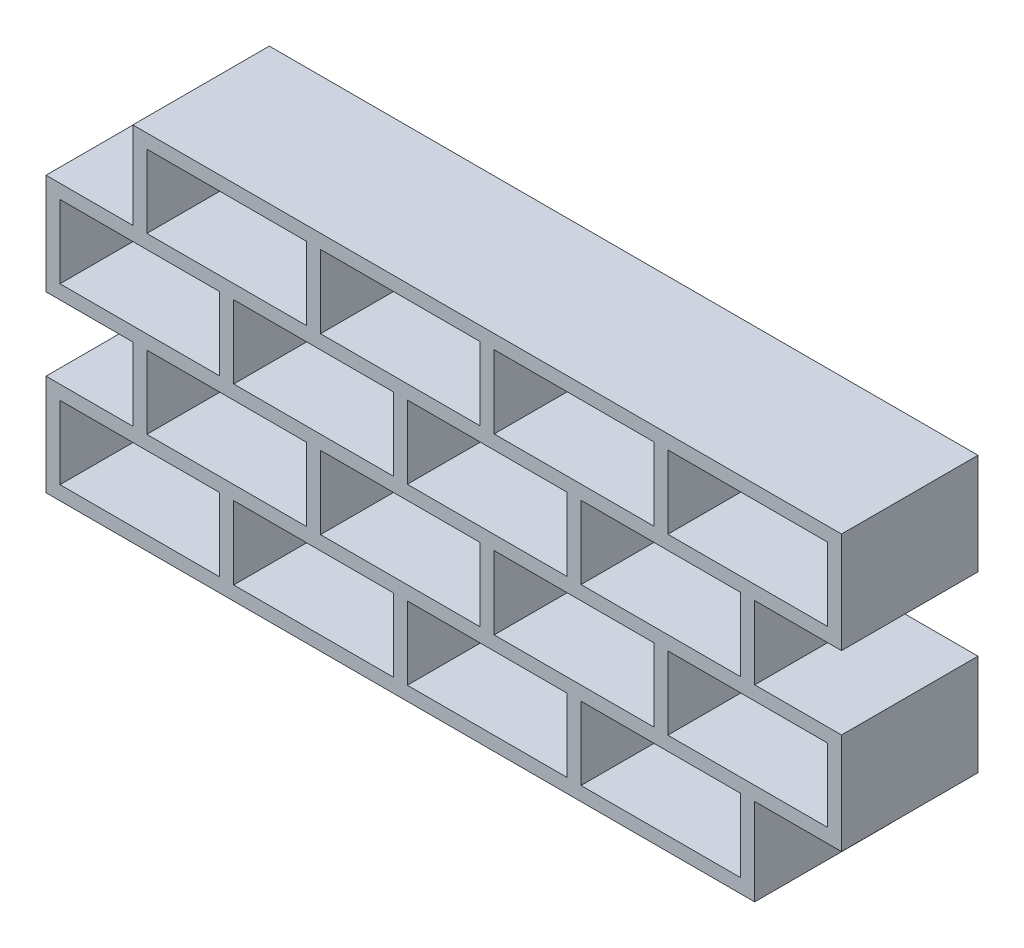
SolidWorks part; units mm, degrees
ref_plane "前视基准面" through (0, 0, 0) normal (0, 0, 1) x (1, 0, 0)
ref_plane "上视基准面" through (0, 0, 0) normal (0, 1, 0) x (1, 0, 0)
ref_plane "右视基准面" through (0, 0, 0) normal (1, 0, 0) x (0, 0, -1)
sketch "草图1" plane through (0, 0, 0) normal (0, 0, 1) x (1, 0, 0)
  line L0 (-2.75, -1.48) -> (2.75, -1.48)
  line L1 (-2.545, -1.275) -> (2.545, -1.275) construction
  line L2 (-2.545, -1.275) -> (-2.545, 1.275) construction
  line L3 (-2.545, 1.275) -> (2.545, 1.275) construction
  line L4 (2.545, -1.275) -> (2.545, 1.275) construction
  line L5 (0, 1.275) -> (0, -1.275) construction
  line L6 (-2.545, 0) -> (2.545, 0) construction
  line L8 (-2.75, 1.48) -> (-0.205, 1.48)
  line L9 (-2.75, -1.48) -> (-2.75, 1.48)
  line L10 (-0.205, 1.07) -> (-0.205, -1.07)
  line L11 (-2.545, -0.205) -> (2.34, -0.205)
  line L12 (-2.34, -1.07) -> (2.34, -1.07)
  line L13 (2.34, -1.07) -> (2.34, 1.07)
  line L14 (-2.34, 1.07) -> (2.34, 1.07)
  line L15 (-2.34, -1.07) -> (-2.34, 1.07)
  line L16 (0.205, 1.07) -> (0.205, -1.07)
  line L17 (-2.545, 0.205) -> (2.34, 0.205)
  line L18 (2.34, -1.48) -> (7.84, -1.48)
  line L20 (2.75, 1.48) -> (4.885, 1.48)
  line L22 (4.885, 1.07) -> (4.885, -1.07)
  line L23 (2.75, -0.205) -> (7.43, -0.205)
  line L24 (2.75, -1.07) -> (7.43, -1.07)
  line L25 (7.43, -1.07) -> (7.43, 1.07)
  line L26 (2.75, 1.07) -> (7.43, 1.07)
  line L27 (2.75, -1.07) -> (2.75, 1.07)
  line L28 (5.295, 1.07) -> (5.295, -1.07)
  line L29 (2.75, 0.205) -> (7.43, 0.205)
  line L30 (2.545, -1.275) -> (7.635, -1.275) construction
  line L31 (2.545, -1.275) -> (2.545, 1.275) construction
  line L32 (2.34, 1.275) -> (7.635, 1.275) construction
  line L33 (7.635, -1.275) -> (7.635, 1.275) construction
  line L34 (5.09, 1.275) -> (5.09, -1.275) construction
  line L35 (2.545, 0) -> (7.635, 0) construction
  line L36 (7.43, -1.48) -> (12.93, -1.48)
  line L38 (7.84, 1.48) -> (9.975, 1.48)
  line L40 (9.975, 1.07) -> (9.975, -1.07)
  line L41 (7.84, -0.205) -> (12.52, -0.205)
  line L42 (7.84, -1.07) -> (12.52, -1.07)
  line L43 (12.52, -1.07) -> (12.52, 1.07)
  line L44 (7.84, 1.07) -> (12.52, 1.07)
  line L45 (7.84, -1.07) -> (7.84, 1.07)
  line L46 (10.385, 1.07) -> (10.385, -1.07)
  line L47 (7.84, 0.205) -> (12.52, 0.205)
  line L48 (7.635, -1.275) -> (12.725, -1.275) construction
  line L49 (7.635, -1.275) -> (7.635, 1.275) construction
  line L50 (7.635, 1.275) -> (12.725, 1.275) construction
  line L51 (12.725, -1.275) -> (12.725, 1.275) construction
  line L52 (10.18, 1.275) -> (10.18, -1.275) construction
  line L53 (7.635, 0) -> (12.725, 0) construction
  line L54 (12.52, -1.48) -> (18.02, -1.48)
  line L55 (18.02, -1.48) -> (18.02, 1.07)
  line L56 (12.93, 1.48) -> (15.065, 1.48)
  line L58 (15.065, 1.07) -> (15.065, -1.07)
  line L59 (12.725, -0.205) -> (17.61, -0.205)
  line L60 (12.93, -1.07) -> (17.61, -1.07)
  line L61 (17.61, -1.07) -> (17.61, 1.07)
  line L62 (12.93, 1.07) -> (17.61, 1.07)
  line L63 (12.93, -1.07) -> (12.93, 1.07)
  line L64 (15.475, 1.07) -> (15.475, -1.07)
  line L65 (12.93, 0.205) -> (17.61, 0.205)
  line L66 (12.725, -1.275) -> (17.815, -1.275) construction
  line L67 (12.725, -1.275) -> (12.725, 1.275) construction
  line L68 (12.725, 1.275) -> (17.815, 1.275) construction
  line L69 (17.815, -1.275) -> (17.815, 1.275) construction
  line L70 (15.27, 1.275) -> (15.27, -1.275) construction
  line L71 (12.725, 0) -> (17.815, 0) construction
  line L72 (2.75, -1.48) -> (2.75, 1.48) construction
  line L73 (-2.545, 0.205) -> (2.545, 0.205) construction
  line L74 (-2.545, -0.205) -> (2.545, -0.205) construction
  line L75 (2.34, -1.07) -> (2.34, 1.07)
  line L76 (2.34, -1.48) -> (2.34, -1.275) [skipped]
  line L77 (2.75, -1.07) -> (2.75, 1.07)
  line L78 (12.52, -1.07) -> (12.52, 1.07)
  line L79 (12.93, -1.07) -> (12.93, 1.07)
  line L80 (12.52, -1.48) -> (12.52, -1.275) [skipped]
  line L81 (7.43, -1.07) -> (7.43, 1.07)
  line L82 (7.43, -1.48) -> (7.43, -1.275) [skipped]
  line L83 (7.84, -1.07) -> (7.84, 1.07)
  line L84 (-0.205, 1.275) -> (-0.205, -1.275) construction
  line L85 (0.205, 1.275) -> (0.205, -1.275) construction
  line L86 (-2.75, 3.62) -> (-0.205, 3.62)
  line L87 (-2.75, 6.58) -> (-0.205, 6.58)
  line L88 (-2.75, 3.62) -> (-2.75, 6.58)
  line L91 (-2.34, 4.03) -> (-0.205, 4.03)
  line L92 (2.34, 4.03) -> (2.34, 4.895)
  line L93 (-2.34, 6.17) -> (-0.205, 6.17)
  line L94 (-2.34, 4.03) -> (-2.34, 4.895)
  line L95 (-0.205, 6.17) -> (0.205, 6.17)
  line L97 (2.75, 3.62) -> (4.885, 3.62)
  line L98 (2.75, 6.58) -> (4.885, 6.58)
  line L99 (-2.34, 5.305) -> (-2.34, 4.895)
  line L100 (-0.205, 4.03) -> (0.205, 4.03)
  line L101 (2.75, 4.03) -> (4.885, 4.03)
  line L102 (7.43, 4.03) -> (7.43, 4.895)
  line L103 (2.75, 6.17) -> (4.885, 6.17)
  line L104 (2.75, 4.03) -> (2.75, 4.895)
  line L105 (4.885, 7.855) -> (4.885, 7.445)
  line L106 (5.295, 7.855) -> (5.295, 7.445)
  line L107 (7.84, 3.62) -> (9.975, 3.62)
  line L108 (7.84, 6.58) -> (9.975, 6.58)
  line L109 (7.43, 8.72) -> (7.84, 8.72)
  line L110 (9.975, 7.855) -> (9.975, 7.445)
  line L111 (7.84, 4.03) -> (9.975, 4.03)
  line L112 (12.52, 4.03) -> (12.52, 4.895)
  line L113 (7.84, 6.17) -> (9.975, 6.17)
  line L114 (7.84, 4.03) -> (7.84, 4.895)
  line L115 (7.43, 6.58) -> (7.84, 6.58)
  line L116 (10.385, 7.855) -> (10.385, 7.445)
  line L117 (12.93, 3.62) -> (15.065, 3.62)
  line L118 (20.155, 2.755) -> (20.155, 3.62)
  line L119 (12.93, 6.58) -> (15.065, 6.58)
  line L120 (12.52, 8.72) -> (12.93, 8.72)
  line L121 (15.065, 7.855) -> (15.065, 7.445)
  line L122 (12.93, 4.03) -> (15.065, 4.03)
  line L123 (17.61, 4.03) -> (17.61, 4.895)
  line L124 (12.93, 6.17) -> (15.065, 6.17)
  line L125 (12.93, 4.03) -> (12.93, 4.895)
  line L126 (12.52, 6.58) -> (12.93, 6.58)
  line L127 (15.475, 7.855) -> (15.475, 7.445)
  line L128 (2.34, 4.03) -> (2.34, 4.895)
  line L129 (2.75, 4.03) -> (2.75, 4.895)
  line L130 (12.52, 4.03) -> (12.52, 4.895)
  line L131 (12.93, 4.03) -> (12.93, 4.895)
  line L132 (7.43, 4.03) -> (7.43, 4.895)
  line L133 (7.84, 4.03) -> (7.84, 4.895)
  line L134 (-2.545, 3.825) -> (2.545, 3.825) construction
  line L135 (-2.545, 3.825) -> (-2.545, 6.375) construction
  line L136 (-2.545, 6.375) -> (2.545, 6.375) construction
  line L137 (2.545, 3.825) -> (2.545, 6.375) construction
  line L138 (17.61, 8.72) -> (18.02, 8.72)
  line L139 (17.61, 6.58) -> (18.02, 6.58)
  line L140 (2.545, 3.825) -> (7.635, 3.825) construction
  line L141 (2.545, 3.825) -> (2.545, 6.375) construction
  line L142 (2.34, 6.375) -> (7.635, 6.375) construction
  line L143 (7.635, 3.825) -> (7.635, 6.375) construction
  line L144 (17.61, 5.305) -> (17.61, 4.895)
  line L145 (15.475, 6.17) -> (15.065, 6.17)
  line L146 (7.635, 3.825) -> (12.725, 3.825) construction
  line L147 (7.635, 3.825) -> (7.635, 6.375) construction
  line L148 (7.635, 6.375) -> (12.725, 6.375) construction
  line L149 (12.725, 3.825) -> (12.725, 6.375) construction
  line L150 (12.93, 5.305) -> (12.93, 4.895)
  line L151 (15.065, 4.03) -> (15.475, 4.03)
  line L152 (12.725, 3.825) -> (17.815, 3.825) construction
  line L153 (12.725, 3.825) -> (12.725, 6.375) construction
  line L154 (12.725, 6.375) -> (17.815, 6.375) construction
  line L155 (17.815, 3.825) -> (17.815, 6.375) construction
  line L156 (12.52, 4.895) -> (12.52, 5.305)
  line L157 (10.385, 6.17) -> (9.975, 6.17)
  line L158 (15.27, 0) -> (15.27, 3.825) construction
  line L159 (7.84, 5.305) -> (7.84, 4.895)
  line L160 (10.385, 4.03) -> (12.52, 4.03)
  line L161 (4.885, 1.48) -> (4.885, 2.345)
  line L162 (0.205, 8.72) -> (2.34, 8.72)
  line L163 (15.475, 6.58) -> (15.475, 7.445)
  line L164 (9.975, 4.03) -> (10.385, 4.03)
  line L165 (2.545, 8.925) -> (2.545, 8.72) construction
  line L166 (20.36, 6.375) -> (20.36, 8.925) construction
  line L167 (0.205, 1.48) -> (2.34, 1.48)
  line L168 (4.885, 1.07) -> (10.385, 1.07)
  line L169 (7.43, 5.305) -> (7.43, 4.895)
  line L170 (20.155, 1.48) -> (20.155, 2.345)
  line L171 (4.885, 6.17) -> (5.295, 6.17)
  line L172 (15.065, 6.58) -> (15.065, 7.445)
  line L173 (10.385, 6.58) -> (10.385, 7.445)
  line L174 (15.27, 1.275) -> (20.36, 1.275) construction
  line L175 (2.75, 5.305) -> (2.75, 4.895)
  line L176 (4.885, 4.03) -> (5.295, 4.03)
  line L177 (10.385, 1.48) -> (10.385, 2.345)
  line L178 (5.295, 6.17) -> (7.43, 6.17)
  line L179 (2.34, 5.305) -> (2.34, 4.895)
  line L180 (0, 1.275) -> (5.09, 1.275) construction
  line L181 (15.27, 1.275) -> (15.27, 3.825) construction
  line L182 (15.27, 3.825) -> (20.36, 3.825) construction
  line L183 (10.18, 6.375) -> (10.18, 8.925) construction
  line L184 (2.34, 3.62) -> (2.75, 3.62)
  line L185 (5.295, 1.48) -> (7.43, 1.48)
  line L186 (9.975, 1.07) -> (15.475, 1.07)
  line L187 (4.885, 9.13) -> (10.385, 9.13)
  line L188 (0.205, 2.755) -> (0.205, 2.345)
  line L189 (15.475, 6.58) -> (17.61, 6.58)
  line L190 (15.065, 6.58) -> (15.065, 7.445)
  line L191 (5.09, 1.275) -> (5.09, 3.825) construction
  line L192 (4.885, 2.755) -> (4.885, 2.345)
  line L193 (9.975, 1.48) -> (9.975, 2.345)
  line L194 (15.475, 3.62) -> (17.61, 3.62)
  line L195 (15.475, 1.48) -> (15.475, 2.345)
  line L196 (0.205, 6.58) -> (0.205, 7.445)
  line L197 (5.295, 8.72) -> (7.43, 8.72)
  line L198 (15.065, 9.13) -> (20.565, 9.13)
  line L199 (2.34, 1.48) -> (2.75, 1.48)
  line L200 (10.18, 1.275) -> (10.18, 3.825) construction
  line L201 (10.18, 3.825) -> (15.27, 3.825) construction
  line L202 (5.295, 4.03) -> (7.43, 4.03)
  line L203 (5.295, 1.48) -> (5.295, 2.345)
  line L204 (5.295, 1.48) -> (5.295, 2.345)
  line L205 (5.295, 6.58) -> (7.43, 6.58)
  line L206 (10.385, 6.17) -> (12.52, 6.17)
  line L207 (5.295, 2.755) -> (5.295, 2.345)
  line L208 (0, 6.375) -> (5.09, 6.375) construction
  line L209 (5.09, 6.375) -> (10.18, 6.375) construction
  line L210 (15.27, 8.925) -> (20.36, 8.925) construction
  line L211 (4.885, 1.48) -> (4.885, 2.345)
  line L212 (7.43, 3.62) -> (7.84, 3.62)
  line L213 (9.975, 2.755) -> (9.975, 2.345)
  line L215 (4.885, 6.58) -> (4.885, 7.445)
  line L216 (10.385, 8.72) -> (12.52, 8.72)
  line L217 (0, 1.275) -> (0, 3.825) construction
  line L218 (7.43, 1.48) -> (7.84, 1.48)
  line L219 (5.09, 6.375) -> (5.09, 8.925) construction
  line L220 (15.27, 6.375) -> (15.27, 8.925) construction
  line L221 (0.205, 1.48) -> (0.205, 2.345)
  line L222 (5.295, 3.62) -> (7.43, 3.62)
  line L223 (10.385, 1.48) -> (12.52, 1.48)
  line L224 (10.385, 6.58) -> (10.385, 7.445)
  line L225 (20.155, 6.58) -> (20.155, 8.72)
  line L226 (4.885, 3.825) -> (10.18, 3.825) construction
  line L227 (20.36, 1.275) -> (20.36, 3.825) construction
  line L228 (17.815, 3.825) -> (17.815, 6.375) construction
  line L229 (10.385, 2.345) -> (10.385, 2.755)
  line L230 (15.065, 1.07) -> (17.61, 1.07)
  line L231 (12.52, 3.62) -> (12.93, 3.62)
  line L232 (15.475, 8.72) -> (17.61, 8.72)
  line L233 (15.475, 6.58) -> (15.475, 7.445)
  line L234 (15.065, 2.755) -> (15.065, 2.345)
  line L235 (12.52, 1.48) -> (12.93, 1.48)
  line L236 (15.27, 6.375) -> (20.36, 6.375) construction
  line L237 (0.205, 4.03) -> (2.34, 4.03)
  line L239 (9.975, 1.48) -> (9.975, 2.345)
  line L241 (10.385, 6.58) -> (12.52, 6.58)
  line L242 (15.475, 6.17) -> (17.61, 6.17)
  line L243 (15.475, 2.755) -> (15.475, 2.345)
  line L244 (15.27, 1.275) -> (15.27, 3.825) construction
  line L245 (10.18, 6.375) -> (15.27, 6.375) construction
  line L246 (15.27, 6.375) -> (15.27, 8.925) construction
  line L247 (17.61, 1.48) -> (18.02, 1.48)
  line L248 (17.61, 3.62) -> (18.02, 3.62)
  line L249 (10.385, 3.62) -> (12.52, 3.62)
  line L250 (9.975, 6.58) -> (9.975, 7.445)
  line L251 (5.295, 6.58) -> (5.295, 7.445)
  line L252 (20.155, 2.755) -> (20.155, 2.345)
  line L253 (4.885, 6.58) -> (4.885, 7.445)
  line L254 (0, 7.65) -> (0.205, 7.65) construction
  line L255 (4.885, 8.925) -> (10.18, 8.925) construction
  line L256 (15.475, 1.48) -> (17.61, 1.48)
  line L257 (15.065, 1.48) -> (15.065, 2.345)
  line L260 (0, 3.825) -> (5.09, 3.825) construction
  line L261 (5.09, 1.275) -> (10.18, 1.275) construction
  line L262 (5.09, 6.375) -> (5.09, 8.925) construction
  line L263 (2.75, 1.48) -> (4.885, 1.48)
  line L264 (0.205, 3.62) -> (2.34, 3.62)
  line L266 (15.475, 1.48) -> (15.475, 2.345)
  line L268 (10.18, 1.275) -> (10.18, 3.825) construction
  line L270 (-0.205, 1.07) -> (5.295, 1.07)
  line L274 (0.205, 6.58) -> (2.34, 6.58)
  line L276 (9.975, 6.58) -> (9.975, 7.445)
  line L279 (15.065, 1.48) -> (15.065, 2.345)
  line L280 (15.475, 4.03) -> (17.61, 4.03)
  line L281 (0.205, 6.58) -> (2.34, 6.58)
  line L285 (10.18, 1.275) -> (15.27, 1.275) construction
  line L289 (10.385, 1.48) -> (10.385, 2.345)
  line L290 (0.205, 6.17) -> (2.34, 6.17)
  line L291 (9.975, 9.13) -> (15.475, 9.13)
  line L292 (5.295, 6.58) -> (5.295, 7.445)
  line L293 (10.18, 6.375) -> (10.18, 8.925) construction
  line L294 (20.155, 7.65) -> (20.36, 7.65) construction
  line L296 (20.565, 1.07) -> (20.565, 4.03)
  line L297 (-0.205, 9.13) -> (5.295, 9.13)
  line L299 (20.565, 6.17) -> (20.565, 9.13)
  line L300 (5.09, 1.275) -> (5.09, 3.825) construction
  line L301 (0, 6.375) -> (0, 8.925) construction
  line L302 (0, 8.925) -> (5.09, 8.925) construction
  line L303 (10.18, 8.925) -> (15.27, 8.925) construction
  line L304 (5.295, 3.62) -> (7.43, 3.62)
  line L305 (5.295, 4.03) -> (7.43, 4.03)
  line L306 (7.84, 4.03) -> (9.975, 4.03)
  line L307 (2.75, 8.72) -> (4.885, 8.72)
  line L310 (0.205, 7.855) -> (0.205, 8.72)
  line L313 (4.885, 7.855) -> (4.885, 8.72)
  line L314 (4.885, 7.855) -> (4.885, 8.72)
  line L315 (5.295, 7.855) -> (5.295, 8.72)
  line L316 (5.295, 7.855) -> (5.295, 8.72)
  line L317 (7.84, 8.72) -> (9.975, 8.72)
  line L322 (9.975, 7.855) -> (9.975, 8.72)
  line L323 (9.975, 7.855) -> (9.975, 8.72)
  line L324 (10.385, 7.855) -> (10.385, 8.72)
  line L325 (10.385, 7.855) -> (10.385, 8.72)
  line L327 (12.93, 8.72) -> (15.065, 8.72)
  line L331 (15.065, 7.855) -> (15.065, 8.72)
  line L332 (15.065, 7.855) -> (15.065, 8.72)
  line L333 (15.475, 7.855) -> (15.475, 8.72)
  line L334 (15.475, 7.855) -> (15.475, 8.72)
  line L335 (18.02, 8.72) -> (20.155, 8.72)
  line L340 (18.02, 6.17) -> (20.565, 6.17)
  line L341 (18.02, 6.58) -> (20.155, 6.58)
  line L342 (15.475, 6.58) -> (17.61, 6.58)
  line L343 (15.475, 6.17) -> (17.61, 6.17)
  line L344 (17.61, 5.305) -> (17.61, 6.17)
  line L349 (12.93, 6.17) -> (15.065, 6.17)
  line L350 (12.93, 6.58) -> (15.065, 6.58)
  line L351 (12.52, 5.305) -> (12.52, 6.17)
  line L352 (12.52, 5.305) -> (12.52, 6.17)
  line L353 (12.93, 5.305) -> (12.93, 6.17)
  line L354 (12.93, 5.305) -> (12.93, 6.17)
  line L355 (10.385, 6.58) -> (12.52, 6.58)
  line L356 (10.385, 6.17) -> (12.52, 6.17)
  line L361 (7.84, 6.17) -> (9.975, 6.17)
  line L362 (7.84, 6.58) -> (9.975, 6.58)
  line L363 (7.43, 5.305) -> (7.43, 6.17)
  line L364 (7.43, 5.305) -> (7.43, 6.17)
  line L365 (7.84, 5.305) -> (7.84, 6.17)
  line L366 (7.84, 5.305) -> (7.84, 6.17)
  line L367 (5.295, 6.58) -> (7.43, 6.58)
  line L368 (5.295, 6.17) -> (7.43, 6.17)
  line L373 (2.75, 6.17) -> (4.885, 6.17)
  line L374 (2.75, 6.58) -> (4.885, 6.58)
  line L375 (2.75, 5.305) -> (2.75, 6.17)
  line L376 (2.75, 5.305) -> (2.75, 6.17)
  line L377 (2.34, 5.305) -> (2.34, 6.17)
  line L378 (2.34, 5.305) -> (2.34, 6.17)
  line L379 (-0.205, 6.58) -> (-0.205, 9.13)
  line L380 (0.205, 6.17) -> (2.34, 6.17)
  line L385 (-2.34, 5.305) -> (-2.34, 6.17)
  line L386 (0.205, 4.03) -> (2.34, 4.03)
  line L387 (0.205, 3.62) -> (2.34, 3.62)
  line L388 (2.75, 4.03) -> (4.885, 4.03)
  line L389 (2.75, 3.62) -> (4.885, 3.62)
  line L390 (7.84, 3.62) -> (9.975, 3.62)
  line L391 (10.385, 4.03) -> (12.52, 4.03)
  line L392 (10.385, 3.62) -> (12.52, 3.62)
  line L393 (12.93, 4.03) -> (15.065, 4.03)
  line L394 (12.93, 3.62) -> (15.065, 3.62)
  line L395 (15.475, 4.03) -> (17.61, 4.03)
  line L397 (15.475, 3.62) -> (17.61, 3.62)
  line L398 (18.02, 4.03) -> (20.565, 4.03)
  line L399 (18.02, 3.62) -> (20.155, 3.62)
  line L400 (18.02, 4.03) -> (18.02, 6.17)
  line L401 (18.02, 3.62) -> (18.02, 3.825) [skipped]
  line L406 (15.475, 2.755) -> (15.475, 3.62)
  line L407 (15.475, 2.755) -> (15.475, 3.62)
  line L408 (15.065, 2.755) -> (15.065, 3.62)
  line L409 (15.065, 2.755) -> (15.065, 3.62)
  line L414 (9.975, 2.755) -> (9.975, 3.62)
  line L415 (9.975, 2.755) -> (9.975, 3.62)
  line L416 (10.385, 2.755) -> (10.385, 3.62)
  line L417 (10.385, 2.755) -> (10.385, 3.62)
  line L422 (4.885, 2.755) -> (4.885, 3.62)
  line L423 (4.885, 2.755) -> (4.885, 3.62)
  line L424 (5.295, 2.755) -> (5.295, 3.62)
  line L425 (5.295, 2.755) -> (5.295, 3.62)
  line L430 (0.205, 2.755) -> (0.205, 3.62)
  line L431 (0.205, 1.48) -> (2.34, 1.48)
  line L432 (-2.75, 1.48) -> (2.75, 1.48) construction
  line L433 (-0.205, 1.48) -> (-0.205, 3.62)
  line L434 (5.295, 1.48) -> (7.43, 1.48)
  line L435 (7.84, 1.48) -> (9.975, 1.48)
  line L436 (10.385, 1.48) -> (12.52, 1.48)
  line L437 (12.93, 1.48) -> (15.065, 1.48)
  line L438 (15.475, 1.48) -> (17.61, 1.48)
  line L439 (18.02, 1.48) -> (20.155, 1.48)
  line L440 (18.02, 1.07) -> (20.565, 1.07)
  line L441 (0.205, 7.855) -> (0.205, 7.445)
  line L442 (2.34, 8.72) -> (2.75, 8.72)
  line L443 (4.885, 7.855) -> (4.885, 7.445)
  line L444 (2.34, 6.58) -> (2.75, 6.58)
  line L445 (2.545, 6.58) -> (2.545, 6.375) construction
  line L446 (4.885, 7.65) -> (5.09, 7.65) construction
  line L447 (-2.34, 4.895) -> (-0.205, 4.895) [skipped]
  line L448 (-2.34, 5.305) -> (-0.205, 5.305) [skipped]
  line L449 (-0.205, 6.17) -> (-0.205, 5.305) [skipped]
  line L450 (0.205, 6.17) -> (0.205, 5.305) [skipped]
  line L451 (0, 5.1) -> (2.545, 5.1) construction
  line L452 (0, 5.1) -> (0, 3.825) construction
  line L453 (2.75, 4.895) -> (4.885, 4.895) [skipped]
  line L454 (2.75, 5.305) -> (4.885, 5.305) [skipped]
  line L455 (4.885, 6.17) -> (4.885, 5.305) [skipped]
  line L456 (5.295, 6.17) -> (5.295, 5.305) [skipped]
  line L457 (5.09, 5.1) -> (7.635, 5.1) construction
  line L458 (5.09, 5.1) -> (5.09, 3.825) construction
  line L459 (7.84, 4.895) -> (9.975, 4.895) [skipped]
  line L460 (7.84, 5.305) -> (9.975, 5.305) [skipped]
  line L461 (9.975, 6.17) -> (9.975, 5.305) [skipped]
  line L462 (10.385, 6.17) -> (10.385, 5.305) [skipped]
  line L463 (10.18, 5.1) -> (12.725, 5.1) construction
  line L464 (10.18, 5.1) -> (10.18, 3.825) construction
  line L465 (12.93, 4.895) -> (15.065, 4.895) [skipped]
  line L466 (12.93, 5.305) -> (15.065, 5.305) [skipped]
  line L467 (15.065, 6.17) -> (15.065, 5.305) [skipped]
  line L468 (15.475, 6.17) -> (15.475, 5.305) [skipped]
  line L469 (15.27, 5.1) -> (17.815, 5.1) construction
  line L470 (15.27, 5.1) -> (15.27, 3.825) construction
  point P0 (0, 0)
  point P22 (5.09, 0)
  point P47 (10.18, 0)
  point P72 (15.27, 0)
  point P102 (2.545, 2.55)
  point P104 (0, 5.1)
  point P120 (5.09, 5.1)
  point P145 (10.18, 5.1)
  point P170 (15.27, 5.1)
  point P233 (7.635, 2.55)
  point P258 (12.725, 2.55)
  point P283 (17.815, 2.55)
  point P313 (2.545, 7.65)
  point P329 (7.635, 7.65)
  point P354 (12.725, 7.65)
  point P379 (17.815, 7.65)
  dimension "D1" = 5.09
  dimension "D2" = 2.55
  dimension "D3" = 0.205
  dimension "D4" = 0.205
  dimension "D5" = 4
  dimension "D7" = 2
extrude "凸台-拉伸1" add sketch "草图1" along normal blind 4 contours L55 L440 L296 L398 L400 L340 L299 L198 L291 L187 L297 L379 L87 L88 L86 L433 L8 L9 L0 L18 L36 L54 L444 L274 L196 L441 L310 L162 L442 L307 L313 L105 L215 L98 L188 L430 L264 L184 L97 L422 L192 L161 L20
